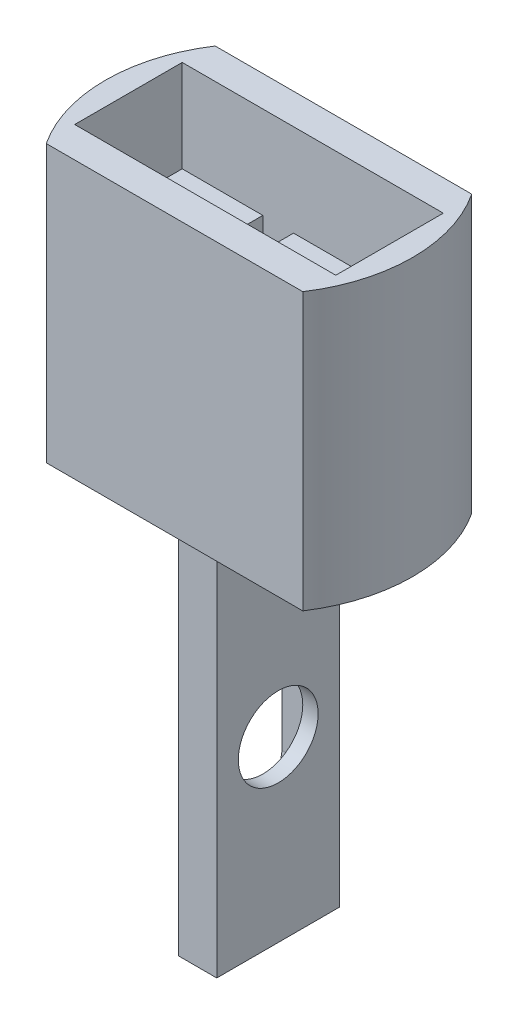
SolidWorks part; units mm, degrees
ref_plane "Front Plane" through (0, 0, 0) normal (0, 0, 1) x (1, 0, 0)
ref_plane "Top Plane" through (0, 0, 0) normal (0, 1, 0) x (1, 0, 0)
ref_plane "Right Plane" through (0, 0, 0) normal (1, 0, 0) x (0, 0, -1)
sketch "Sketch3" plane through (0, 0, 0) normal (0, 1, 0) x (1, 0, 0)
  circle A0 centre (0, 0) radius 10
  dimension "D1" = 20
extrude "Boss-Extrude1" add sketch "Sketch3" along normal blind 18
sketch "Sketch4" plane through (0, 0, 0) normal (0, -1, 0) x (-1, 0, 0)
  line L1 (1.25, 4) -> (-1.25, 4)
  line L2 (1.25, 4) -> (1.25, -4)
  line L3 (1.25, -4) -> (-1.25, -4)
  line L4 (-1.25, 4) -> (-1.25, -4)
  line L5 (1.25, 4) -> (-1.25, -4) construction
  line L6 (1.25, -4) -> (-1.25, 4) construction
  point P0 (0, 0)
  dimension "D1" = 2.5
  dimension "D2" = 8
  dimension "D3" = 0
extrude "Boss-Extrude2" add sketch "Sketch4" along normal blind 25
sketch "Sketch5" plane through (1.25, 0, 0) normal (1, 0, 0) x (0, 0, -1)
  line L0 (-4, -25) -> (4, -25) construction
  circle A0 centre (0, -13.4) radius 2.6
  dimension "D1" = 5.2
  dimension "D2" = 11.6
extrude "Cut-Extrude1" cut sketch "Sketch5" against normal up to next
sketch "Sketch7" plane through (0, 18, 0) normal (0, 1, 0) x (1, 0, 0)
  line L0 (-10, 0) -> (10, 0) construction
  line L1 (-8.5, -3.5) -> (8.5, -3.5)
  line L2 (-8.5, -3.5) -> (-8.5, 3.5)
  line L3 (-8.5, 3.5) -> (8.5, 3.5)
  line L4 (8.5, -3.5) -> (8.5, 3.5)
  circle A0 centre (0, 0) radius 10 construction
  point P4 (-8.5, 0)
  dimension "D1" = 7
  dimension "D2" = 17
  dimension "D3" = 1.5
extrude "Cut-Extrude3" cut sketch "Sketch7" against normal blind 6
sketch "Sketch8" plane through (0, 12, 0) normal (0, 1, 0) x (1, 0, 0)
  line L0 (8.5, 0) -> (-1.25, 0) construction
  line L1 (8.5, -3.5) -> (8.5, 3.5) construction
  line L2 (8.5, 3.5) -> (-8.5, 3.5) construction
  line L3 (-1.25, 3.5) -> (-3.25, 3.5)
  line L4 (-1.25, 3.5) -> (-1.25, -3.5)
  line L5 (-1.25, -3.5) -> (-3.25, -3.5)
  line L6 (-3.25, 3.5) -> (-3.25, -3.5)
  line L7 (-8.5, 3.5) -> (-8.5, -3.5) construction
  dimension "D1" = 9.75
  dimension "D2" = 2
extrude "Cut-Extrude4" cut sketch "Sketch8" against normal blind 4
sketch "Sketch11" plane through (-1.25, 0, 0) normal (-1, 0, 0) x (0, 0, 1)
  line L0 (-2.75, -2.9) -> (2.75, -23.9) construction
  line L1 (2.75, -23.9) -> (-2.75, -23.9)
  line L2 (2.75, -23.9) -> (2.75, -2.9)
  line L3 (2.75, -2.9) -> (-2.75, -2.9)
  line L4 (-2.75, -23.9) -> (-2.75, -2.9)
  line L5 (-2.75, -23.9) -> (2.75, -2.9) construction
  line L6 (-2.6, -13.4) -> (2.6, -13.4) construction
  line L7 (0, -10.8) -> (0, -16) construction
  circle A0 centre (0, -13.4) radius 2.6 construction
  point P11 (0, -13.4)
  point P12 (0, -13.4)
  dimension "D1" = 5.5
  dimension "D2" = 21
extrude "Cut-Extrude7" cut sketch "Sketch11" against normal blind 1.5
sketch "Sketch9" plane through (0, 0, 0) normal (0, -1, 0) x (1, 0, 0)
  line L0 (8.3516, -5.5) -> (-8.3516, -5.5)
  line L1 (-1.25, -4) -> (1.25, -4) construction
  line L2 (0, -5.5) -> (0, -4) construction
  line L3 (8.3516, 5.5) -> (-8.3516, 5.5)
  line L4 (0, 4) -> (0, 5.5) construction
  line L5 (1.25, 4) -> (-1.25, 4) construction
  circle A0 centre (0, 0) radius 10 construction
  arc A1 (8.3516, -5.5) -> (-8.3516, -5.5) centre (0, 0) cw
  arc A2 (-8.3516, 5.5) -> (8.3516, 5.5) centre (0, 0) cw
  dimension "D1" = 1.5
extrude "Cut-Extrude5" cut sketch "Sketch9" against normal blind 43
sketch "Sketch10" plane through (-1.25, 0, 0) normal (-1, 0, 0) x (0, 0, 1)
  line L0 (-2.75, -23.9) -> (-2.75, -16.8)
  line L1 (-2.75, -16.8) -> (-1.5, -23.9)
  line L2 (-1.5, -23.9) -> (-2.75, -23.9)
  line L3 (-2.75, -13.4) -> (2.75, -13.4) construction
  line L4 (0, -23.9) -> (0, -2.9) construction
  line L5 (1.5, -23.9) -> (2.75, -23.9)
  line L6 (2.75, -16.8) -> (1.5, -23.9)
  line L7 (2.75, -23.9) -> (2.75, -16.8)
  line L8 (2.75, -2.9) -> (2.75, -10)
  line L9 (2.75, -10) -> (1.5, -2.9)
  line L10 (1.5, -2.9) -> (2.75, -2.9)
  line L11 (-1.5, -2.9) -> (-2.75, -2.9)
  line L12 (-2.75, -10) -> (-1.5, -2.9)
  line L13 (-2.75, -2.9) -> (-2.75, -10)
  line L14 (0, -10.8) -> (0, -16) construction
  line L15 (2.6, -13.4) -> (-2.6, -13.4) construction
  line L16 (4, 0) -> (-4, 0) construction
  line L17 (-4, -25) -> (-4, 0) construction
  circle A0 centre (0, -13.4) radius 2.6 construction
  dimension "D1" = 1.25
  dimension "D2" = 2.5
  dimension "D3" = 2.9
  dimension "D4" = 10
extrude "Boss-Extrude3" add sketch "Sketch10" against normal blind 1.5
